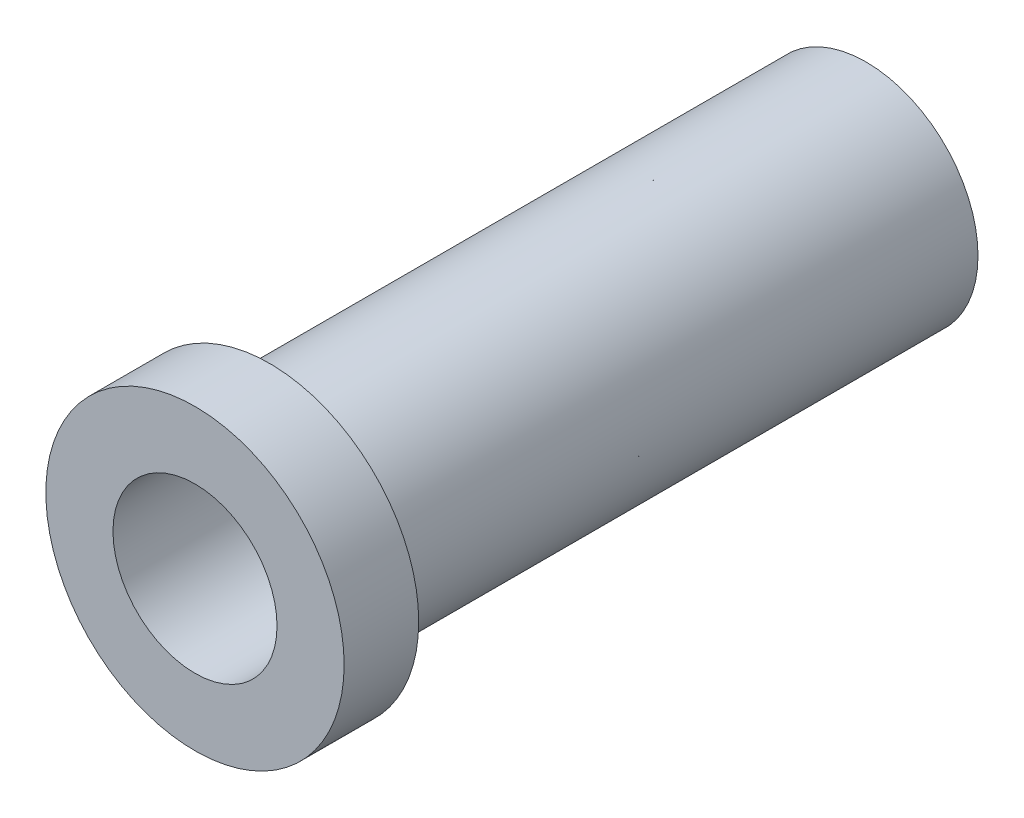
SolidWorks part; units mm, degrees
ref_plane "Front Plane" through (0, 0, 0) normal (0, 0, 1) x (1, 0, 0)
ref_plane "Top Plane" through (0, 0, 0) normal (0, 1, 0) x (1, 0, 0)
ref_plane "Right Plane" through (0, 0, 0) normal (1, 0, 0) x (0, 0, -1)
sketch "Sketch1" plane through (0, 0, 0) normal (0, 0, 1) x (1, 0, 0)
  circle A0 centre (0, 0) radius 5.5
  circle A1 centre (0, 0) radius 10
  dimension "D1" = 11
  dimension "D2" = 20
extrude "Boss-Extrude1" add sketch "Sketch1" along normal blind 5
sketch "Sketch2" plane through (0, 0, 0) normal (0, 0, -1) x (-1, 0, 0)
  circle A0 centre (0, 0) radius 5.5
  circle A1 centre (0, 0) radius 7.5
  dimension "D1" = 11
  dimension "D2" = 15
extrude "Boss-Extrude2" add sketch "Sketch2" along normal blind 40 contours A1 | A0
